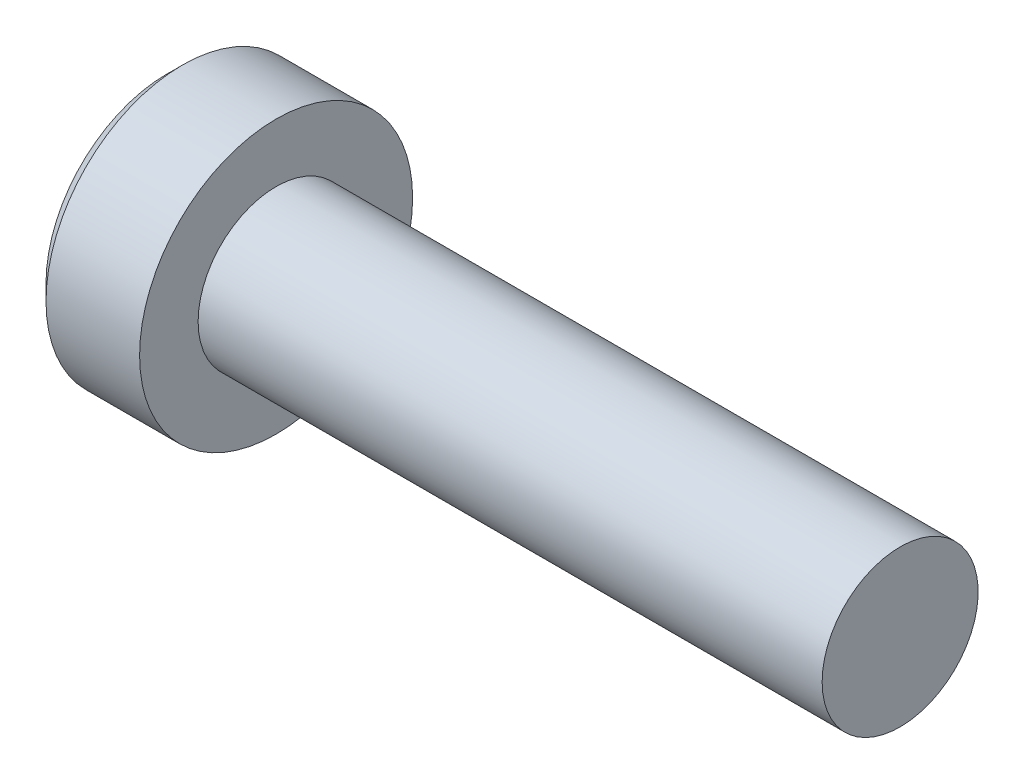
SolidWorks part; units mm, degrees
ref_plane "Front Plane" through (0, 0, 0) normal (0, 0, 1) x (1, 0, 0)
ref_plane "Top Plane" through (0, 0, 0) normal (0, 1, 0) x (1, 0, 0)
ref_plane "Right Plane" through (0, 0, 0) normal (1, 0, 0) x (0, 0, -1)
sketch "Sketch1" plane through (0, 0, 0) normal (0, 0, 1) x (1, 0, 0)
  line L0 (-2.8, 0) -> (16, 0) construction
  line L1 (16, 0) -> (16, 2)
  line L2 (16, 2) -> (0, 2)
  line L3 (0, 2) -> (0, 3.5)
  line L4 (0, 3.5) -> (-2.8, 3.5)
  line L5 (-2.8, 3.5) -> (-2.8, 0)
  line L6 (-2.8, 0) -> (16, 0)
  dimension "MSM_47" = 4
  dimension "MSM_48" = 7
  dimension "MSM_49" = 16
  dimension "MSM_50" = 2.8
revolve "Revolve1" add sketch "Sketch1" angle 360 about L0
cosmetic thread "Thread6" parameters "ATD"=3.242
sketch "Sketch2" plane through (-2.8, 0, 0) normal (-1, 0, 0) x (0, 0, 1)
  line L1 (0, 1.7321) -> (-1.5, 0.866)
  line L2 (-1.5, 0.866) -> (-1.5, -0.866)
  line L3 (-1.5, -0.866) -> (0, -1.7321)
  line L4 (0, -1.7321) -> (1.5, -0.866)
  line L5 (1.5, -0.866) -> (1.5, 0.866)
  line L6 (1.5, 0.866) -> (0, 1.7321)
  circle A0 centre (0, 0) radius 1.5 construction
  dimension "MSM_51" = 3
extrude "Cut-Extrude1" cut sketch "Sketch2" against normal blind 2
sketch "Sketch3" plane through (0, 0, 0) normal (0, 0, 1) x (1, 0, 0)
  line L0 (-0.8, 0) -> (0.066, 0) construction
  line L1 (-0.8, -0.866) -> (-0.8, 0.866) construction
  line L2 (0.066, 0) -> (-0.8, 1.5)
  line L3 (-0.8, 0.866) -> (-0.8, 1.7321) construction
  line L4 (-0.8, 1.5) -> (-0.8, 0)
  line L5 (-0.8, 0) -> (0.066, 0)
  dimension "FIX_2" = 30
  dimension "FIX_3" = 3
revolve "Cut-Revolve1" cut sketch "Sketch3" angle 360 about L0
chamfer "Chamfer1" distance 0.4 1 edges at (-2.8, 0, 3.5)
equation "\"FIX_5@Chamfer1\" = \"MSM_47@Sketch1\" / 10"
equation "\"FIX_3@Sketch3\" = \"MSM_51@Sketch2\""
